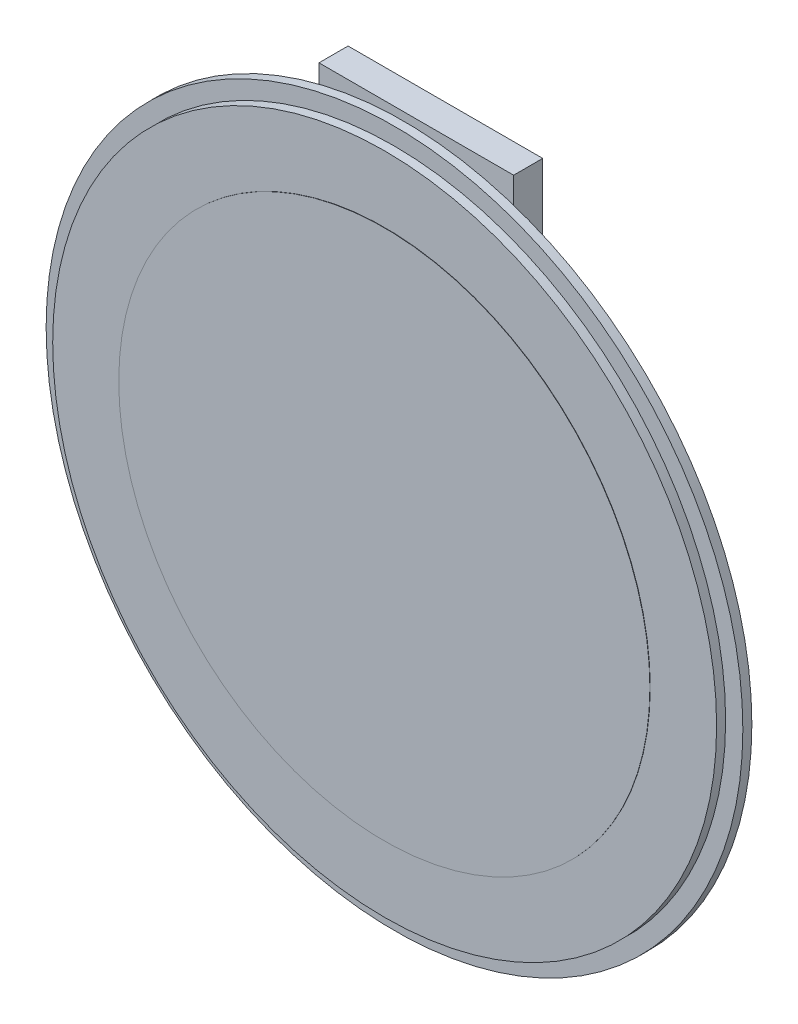
SolidWorks part; units mm, degrees
ref_plane "前视基准面" through (0, 0, 0) normal (0, 0, 1) x (1, 0, 0)
ref_plane "上视基准面" through (0, 0, 0) normal (0, 1, 0) x (1, 0, 0)
ref_plane "右视基准面" through (0, 0, 0) normal (1, 0, 0) x (0, 0, -1)
sketch "草图1" plane through (0, 0, 0) normal (0, 0, 1) x (1, 0, 0)
  circle A0 centre (0, 0) radius 21.25
  dimension "D2" = 42.5
extrude "凸台-拉伸2" add sketch "草图1" along normal blind 0.55 contours A0
sketch "草图4" plane through (0, 0, 0.55) normal (0, 0, 1) x (1, 0, 0)
  circle A0 centre (0, 0) radius 20.25
  point P3 (0, 0)
  dimension "D1" = 40.5
extrude "凸台-拉伸5" add sketch "草图4" along normal blind 0.55 from offset 0.05 separate body
sketch "草图5" plane through (0, 0, 1.15) normal (0, 0, 1) x (1, 0, 0)
  circle A0 centre (0, 0) radius 16.2
  dimension "D1" = 32.4
sketch "草图12" plane through (0, 0, 0) normal (0, 0, -1) x (-1, 0, 0)
  line L0 (-5.4463, -19.945) -> (4.5712, -19.945) construction
  line L1 (0, 17.795) -> (-22.6059, 17.795) construction
  line L2 (0, 0) -> (0, -26.3128) construction
  line L3 (-6.62, -19.945) -> (6.62, -19.945)
  line L4 (-7.1417, -18.5118) -> (7.1417, -18.5118) construction
  line L5 (7.1417, -18.5118) -> (6.62, -19.945)
  line L6 (-7.1417, -18.5118) -> (-6.62, -19.945)
  line L7 (9.4299, -15.091) -> (0, 0) construction
  arc A0 (9.4299, -15.091) -> (-9.4299, -15.091) centre (0, 0) ccw
  arc A1 (7.1417, -18.5118) -> (9.4299, -15.091) centre (15.2598, -21.4665) cw
  arc A2 (9.4299, -15.091) -> (7.1417, -18.5118) centre (15.2598, -21.4665) ccw
  arc A3 (-7.1417, -18.5118) -> (-9.4299, -15.091) centre (-15.2598, -21.4665) ccw
  point P6 (-6.62, -19.945)
  point P10 (6.62, -19.945)
  point P11 (0, -18.5118)
  point P17 (0, -18.5118)
  point P19 (9.4299, -15.091)
  point P23 (0, 0)
  dimension "D1" = 35.59
  dimension "D2" = 37.74
  dimension "D3" = 6.62
  dimension "D4" = 1.4332
  dimension "D5" = 110
  dimension "D6" = 32
extrude "凸台-拉伸6" add sketch "草图12" along normal blind 1.85 contours A3 L6 L3 L5 A1 A0
sketch "草图13" plane through (0, -19.945, 0) normal (0, -1, 0) x (1, 0, 0)
  line L0 (0, 0) -> (0, -5.1653) construction
  line L2 (6.62, 0) -> (-6.62, 0) construction
  line L3 (6.62, 0) -> (-6.62, 0)
  line L4 (-6.07, -1.25) -> (6.07, -1.25)
  line L5 (-6.07, -1.25) -> (-6.07, -1.5)
  line L6 (-6.07, -1.5) -> (6.07, -1.5)
  line L7 (6.07, -1.25) -> (6.07, -1.5)
  line L8 (-6.07, -1.25) -> (6.07, -1.5) construction
  line L9 (-6.07, -1.5) -> (6.07, -1.25) construction
  point P3 (0, -1.375)
  point P9 (0, 0)
  dimension "D1" = 1.25
  dimension "D2" = 0.25
  dimension "D3" = 12.14
sketch "草图14" plane through (0, 0, 0) normal (1, 0, 0) x (0, 0, -1)
  line L1 (1.85, -19.945) -> (0, -19.945) construction
  line L2 (1.85, -15.091) -> (1.85, 17.795) construction
  line L3 (1.85, 17.795) -> (0, 17.795) construction
  line L4 (1.85, -19.945) -> (0, -19.945) construction
  line L5 (1.85, -15.091) -> (1.85, 17.795) construction
  line L6 (1.375, -19.945) -> (1.375, -20.5875)
  line L7 (2.7, -20.5875) -> (2.7, 17.795)
  line L8 (-0.55, -21.25) -> (0, -21.25) construction
  line L9 (-0.55, -21.25) -> (0, -21.25) construction
  line L10 (1.85, 17.795) -> (0, 17.795) construction
  arc A0 (1.375, -20.5875) -> (2.7, -20.5875) centre (2.0375, -20.5875) ccw
  point P0 (3.0035, -20.4357)
  point P12 (1.375, -19.945)
  point P18 (0, 0)
  dimension "D1" = 0.85
sweep "扫描2" add profiles "草图13" path "草图14"
sketch "草图15" plane through (0, 0, -2.825) normal (0, 0, -1) x (-1, 0, 0)
  line L0 (-6.07, -12.5875) -> (-2.93, -12.5875)
  line L1 (-2.93, -12.5875) -> (-2.93, 17.795)
  line L2 (6.07, 3.9125) -> (5.07, 3.9125)
  line L3 (5.07, 3.9125) -> (5.07, 17.795)
  line L4 (6.07, 17.795) -> (-6.07, 17.795)
  line L5 (-6.07, 17.795) -> (-6.07, -20.5875)
  line L6 (-6.07, -20.5875) -> (6.07, -20.5875)
  line L7 (6.07, -20.5875) -> (6.07, 17.795)
  line L8 (6.07, 17.795) -> (-6.07, 17.795)
  line L9 (-6.07, 17.795) -> (-6.07, -20.5875)
  line L10 (-6.07, -20.5875) -> (6.07, -20.5875)
  line L11 (6.07, -20.5875) -> (6.07, 17.795)
  line M9 (6.07, 17.795) -> (-6.07, 17.795)
  line M10 (-6.07, 17.795) -> (-6.07, -20.5875)
  line M12 (6.07, -20.5875) -> (6.07, 17.795)
  dimension "D2" = 8
  dimension "D3" = 1
  dimension "D4" = 24.5
  dimension "D5" = 8
  dimension "D1" = 0
extrude "切除-拉伸1" cut sketch "草图15" against normal up to next (0.25 mm away) contours L3 L2 M12 M9 | L0 L1 M9 M10
fillet "圆角3" radius 0.35 6 edges at (-6.07, 3.9125, -2.7) (-5.07, 3.9125, -2.7) (-5.07, 17.795, -2.7) (2.93, 17.795, -2.7) (2.93, -12.5875, -2.7) (6.07, -12.5875, -2.7)
sketch "草图18" plane through (6.07, 0, 0) normal (1, 0, 0) x (0, 0, -1)
  line L2 (2.825, -20.5875) -> (2.575, -20.5875)
  line L3 (1.5, -20.5875) -> (1.25, -20.5875)
  line L4 (2.825, -20.5875) -> (2.7375, -20.5875) construction
  line L5 (1.5, -20.5875) -> (1.4375, -20.5875) construction
  line L6 (1.3375, -20.5875) -> (1.25, -20.5875) construction
  line L7 (2.6375, -20.5875) -> (2.575, -20.5875) construction
  line L8 (1.25, -20.5875) -> (1.3375, -20.5875)
  line L9 (1.4375, -20.5875) -> (1.5, -20.5875)
  line L10 (2.575, -20.5875) -> (2.6375, -20.5875)
  line L11 (2.7375, -20.5875) -> (2.825, -20.5875)
  arc A0 (1.4375, -20.5875) -> (2.6375, -20.5875) centre (2.0375, -20.5875) ccw
  arc A1 (2.7375, -20.5875) -> (1.3375, -20.5875) centre (2.0375, -20.5875) cw
  arc A2 (1.25, -20.5875) -> (2.825, -20.5875) centre (2.0375, -20.5875) ccw
  arc A3 (1.5, -20.5875) -> (2.575, -20.5875) centre (2.0375, -20.5875) ccw
  arc A4 (1.25, -20.5875) -> (2.825, -20.5875) centre (2.0375, -20.5875) ccw
  arc A5 (1.5, -20.5875) -> (2.575, -20.5875) centre (2.0375, -20.5875) ccw construction
  arc M8 (1.25, -20.5875) -> (2.825, -20.5875) centre (2.0375, -20.5875) ccw
  line M9 (2.825, -20.5875) -> (2.575, -20.5875)
  arc M10 (2.575, -20.5875) -> (1.5, -20.5875) centre (2.0375, -20.5875) cw
  line M11 (1.5, -20.5875) -> (1.25, -20.5875)
  dimension "D2" = 0.6
  dimension "D3" = 0.7
  dimension "D1" = 0
extrude "切除-拉伸2" cut sketch "草图18" against normal up to next (12.14 mm away) contours A0 M11 M9 M10 | A1 M9 M11 M8
fillet "圆角4" radius 0.03 8 edges at (0, -20.5875, -2.7375) (0, -20.5875, -1.3375) (0, -20.5875, -1.4375) (0, -20.5875, -2.6375) (0, -20.5875, -1.5) (0, -20.5875, -1.25) (0, -20.5875, -2.575) (0, -20.5875, -2.825)
sketch "草图21" plane through (0, 0, -2.825) normal (0, 0, -1) x (-1, 0, 0)
  line L1 (-4.8667, 14.481) -> (7.0067, 14.481)
  line L2 (-4.8667, 14.481) -> (-4.8667, 19.8958)
  line L3 (-4.8667, 19.8958) -> (7.0067, 19.8958)
  line L4 (7.0067, 14.481) -> (7.0067, 19.8958)
  line L5 (-4.8667, 14.481) -> (7.0067, 19.8958) construction
  line L6 (-4.8667, 19.8958) -> (7.0067, 14.481) construction
  point P0 (1.07, 17.1884)
  point P5 (0, 0)
extrude "凸台-拉伸9" add sketch "草图21" along normal blind 0.8 and the other way up to surface (0.975 mm away) separate body other way up to face at (0, -12.3222, -1.85)
sketch "草图22" plane through (0, 0, -2.825) normal (0, 0, -1) x (-1, 0, 0)
  line L1 (5.72, 3.5625) -> (-2.5377, 3.5625)
  line L2 (5.72, 3.5625) -> (5.72, -8.4375)
  line L3 (5.72, -8.4375) -> (-2.5377, -8.4375)
  line L4 (-2.5377, 3.5625) -> (-2.5377, -8.4375)
  dimension "D1" = 8.2577
  dimension "D2" = 12
extrude "凸台-拉伸10" add sketch "草图22" along normal blind 0.6
extrude "凸台-拉伸11" add sketch "草图5" along normal blind 0.02 separate body
